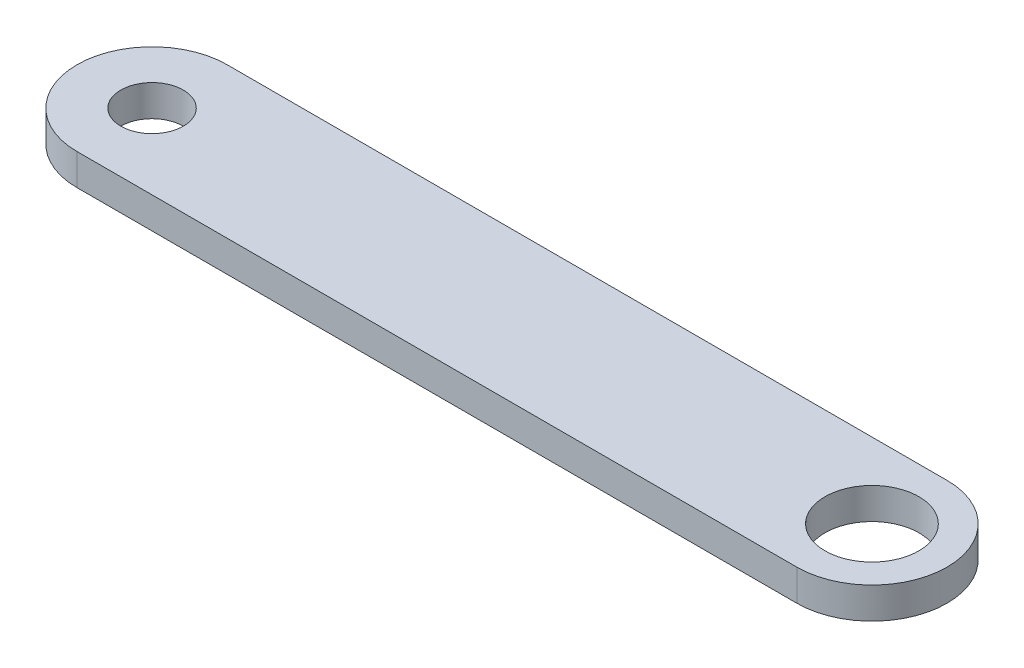
SolidWorks part; units mm, degrees
ref_plane "Front Plane" through (0, 0, 0) normal (0, 0, 1) x (1, 0, 0)
ref_plane "Top Plane" through (0, 0, 0) normal (0, 1, 0) x (1, 0, 0)
ref_plane "Right Plane" through (0, 0, 0) normal (1, 0, 0) x (0, 0, -1)
sketch "Sketch1" plane through (0, 0, 0) normal (0, 1, 0) x (1, 0, 0)
  line L0 (-57.5, 0) -> (57.5, 0) construction
  line L1 (-57.5, 12) -> (57.5, 12)
  line L2 (-57.5, -12) -> (57.5, -12)
  arc A0 (-57.5, 12) -> (-57.5, -12) centre (-57.5, 0) ccw
  arc A1 (57.5, -12) -> (57.5, 12) centre (57.5, 0) ccw
  circle A2 centre (-57.5, 0) radius 5
  circle A3 centre (57.5, 0) radius 7.5
  point P3 (0, 0)
  dimension "D2" = 12
  dimension "D3" = 10
  dimension "D4" = 15
  dimension "D1" = 115
extrude "Boss-Extrude1" add sketch "Sketch1" along normal blind 5
scale "Scale2" scale about centroid uniform scaling yes scale factor 0.2004
